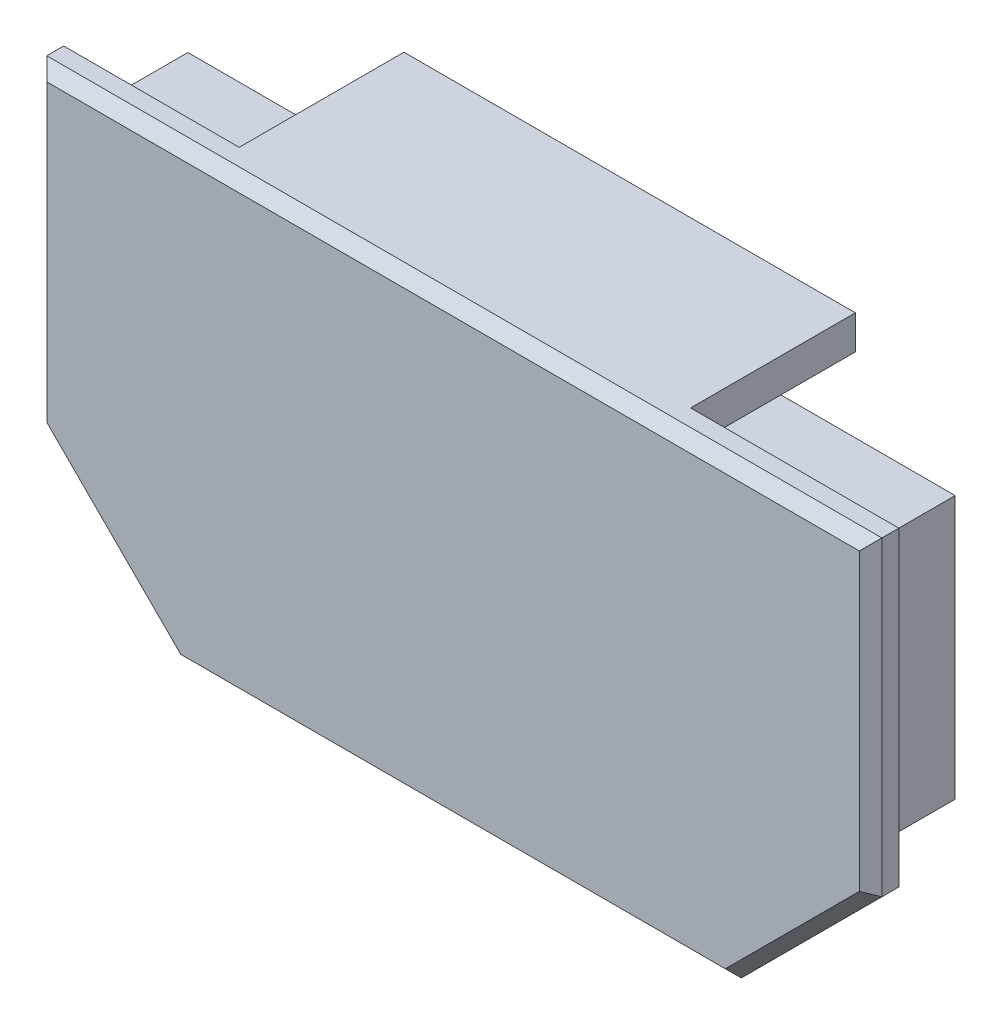
SolidWorks part; units mm, degrees
ref_plane "Front Plane" through (0, 0, 0) normal (0, 0, 1) x (1, 0, 0)
ref_plane "Top Plane" through (0, 0, 0) normal (0, 1, 0) x (1, 0, 0)
ref_plane "Right Plane" through (0, 0, 0) normal (1, 0, 0) x (0, 0, -1)
sketch "Servo Bracket Reference" plane through (0, 0, 0) normal (0, 0, 1) x (1, 0, 0)
  line L0 (-37, 20) -> (37, 20) construction
  line L1 (-37, -3.3) -> (-20.3, -20) construction
  line L34 (-37, 20) -> (-37, -7.5426) construction
  line L35 (-37, -7.5426) -> (-24.5426, -20) construction
  line L36 (-24.5426, -20) -> (24.5426, -20) construction
  line L37 (24.5426, -20) -> (37, -7.5426) construction
  line L38 (37, -7.5426) -> (37, 20) construction
  point P0 (0, 20)
  point P4 (0, 0)
  dimension "D3" = 74
  dimension "D1" = 40
  dimension "D5" = 20
  dimension "D2" = 3
  dimension "D4" = 16.7
sketch "Sketch2" plane through (0, 0, 0) normal (0, 0, 1) x (1, 0, 0)
  line L18 (37, -7.5426) -> (37, 20) construction
  line L19 (24.5426, -20) -> (37, -7.5426) construction
  line L20 (-24.5426, -20) -> (24.5426, -20) construction
  line L21 (-37, 20) -> (-37, -7.5426) construction
  line L22 (-37, -7.5426) -> (-24.5426, -20) construction
  line L23 (-37, 20) -> (37, 20) construction
  line L24 (37, -7.5426) -> (37, 20) construction
  line L25 (24.5426, -20) -> (37, -7.5426) construction
  line L26 (-24.5426, -20) -> (24.5426, -20) construction
  line L27 (-37, 20) -> (-37, -7.5426) construction
  line L28 (-37, -7.5426) -> (-24.5426, -20) construction
  line L29 (-37, 20) -> (37, 20) construction
  line L36 (34, -6.3) -> (34, 17)
  line L37 (-34, 17) -> (34, 17)
  line L38 (-34, 17) -> (-34, -6.3)
  line L39 (-34, -6.3) -> (-23.3, -17)
  line L40 (-23.3, -17) -> (23.3, -17)
  line L41 (23.3, -17) -> (34, -6.3)
  line L42 (32, -5.4716) -> (32, 15)
  line L43 (-32, 15) -> (32, 15)
  line L44 (-32, 15) -> (-32, -5.4716)
  line L45 (-32, -5.4716) -> (-22.4716, -15)
  line L46 (-22.4716, -15) -> (22.4716, -15)
  line L47 (22.4716, -15) -> (32, -5.4716)
  dimension "D1" = 3
  dimension "D2" = 2
extrude "Press Fit Wall Extrude" add sketch "Sketch2" against normal blind 8
sketch "Sketch3" plane through (0, 0, 0) normal (0, 0, 1) x (1, 0, 0)
  line L6 (24.5426, -20) -> (37, -7.5426) construction
  line L7 (37, -7.5426) -> (37, 20) construction
  line L8 (-37, 20) -> (37, 20) construction
  line L9 (-37, 20) -> (-37, -7.5426) construction
  line L10 (-37, -7.5426) -> (-24.5426, -20) construction
  line L11 (-24.5426, -20) -> (24.5426, -20) construction
  line L24 (24.5426, -20) -> (37, -7.5426)
  line L25 (37, -7.5426) -> (37, 20)
  line L26 (-37, 20) -> (37, 20)
  line L27 (-37, 20) -> (-37, -7.5426)
  line L28 (-37, -7.5426) -> (-24.5426, -20)
  line L29 (-24.5426, -20) -> (24.5426, -20)
extrude "Main Lid Extrude" add sketch "Sketch3" along normal blind 2.5
chamfer "Main Lid Chamfer" distance 1 angle 45 6 edges at (37, 6.2287, 2.5) (30.7713, -13.7713, 2.5) (-30.7713, -13.7713, 2.5) (-37, 6.2287, 2.5) (0, 20, 2.5) (0, -20, 2.5)
sketch "Sketch4" plane through (0, -20, 0) normal (0, -1, 0) x (1, 0, 0)
  line L0 (-4, 0) -> (4, 0)
  line L5 (-37, 0) -> (37, 0) construction
  line L6 (4, 0) -> (2.2679, 1)
  line L7 (2.2679, 1) -> (-2.2679, 1)
  line L8 (-2.2679, 1) -> (-4, 0)
  point P4 (0, 0)
  point P8 (1.8704, 0.8792)
  dimension "D1" = 8
  dimension "D2" = 30
  dimension "D3" = 1
extrude "Main Lid Tab Cut" cut sketch "Sketch4" against normal up to surface (3 mm away) up to face at (0, -17, -4)
sketch "Sketch5" plane through (0, 0, 0) normal (0, 0, -1) x (-1, 0, 0)
  line L0 (-37, 20) -> (37, 20) construction
  line L1 (-18.55, 20) -> (21.45, 20)
  line L2 (-18.55, 20) -> (-18.55, 17)
  line L3 (-18.55, 17) -> (21.45, 17)
  line L4 (21.45, 20) -> (21.45, 17)
  line L5 (-34, 17) -> (34, 17) construction
  line L7 (-37, -7.5426) -> (-37, 20) construction
  dimension "D1" = 40
  dimension "D2" = 18.45
extrude "Servo Wall Extrude" add sketch "Sketch5" along normal blind 14.6
equation "\"D5@Servo Bracket Reference\"=\"D1@Servo Bracket Reference\"/2"
